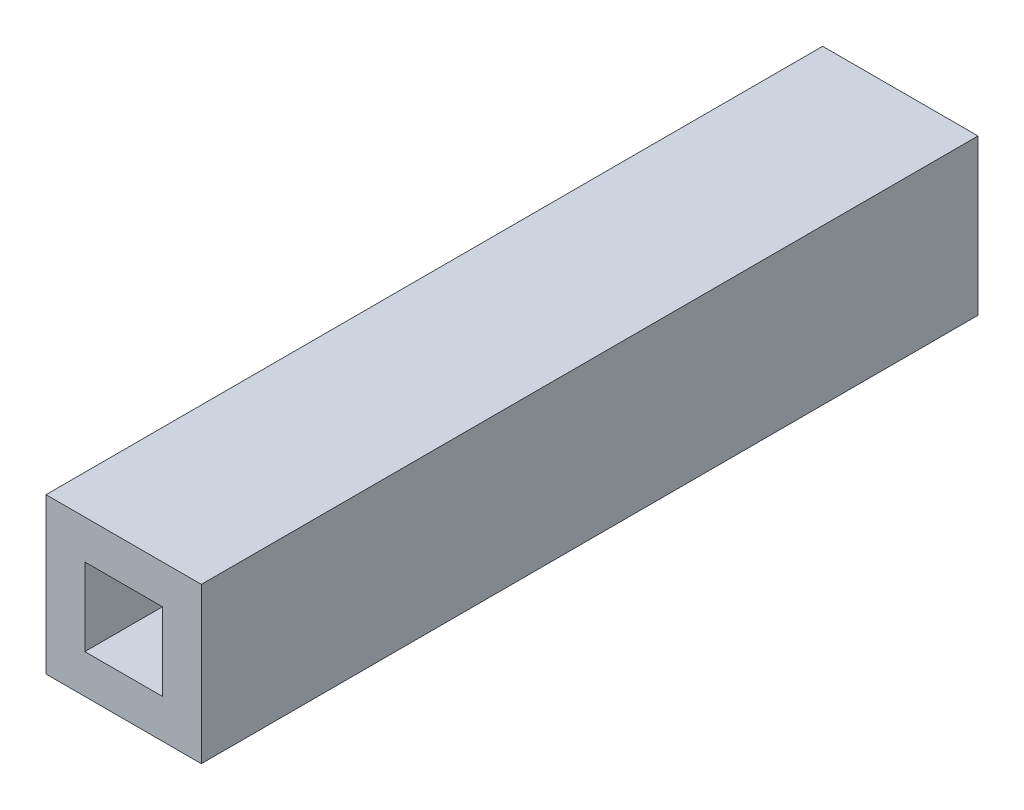
SolidWorks part; units mm, degrees
material "6063-O"
ref_plane "Front Plane" through (0, 0, 0) normal (0, 0, 1) x (1, 0, 0)
ref_plane "Top Plane" through (0, 0, 0) normal (0, 1, 0) x (1, 0, 0)
ref_plane "Right Plane" through (0, 0, 0) normal (1, 0, 0) x (0, 0, -1)
sketch "Sketch1" plane through (0, 0, 0) normal (0, 0, 1) x (1, 0, 0)
  line L1 (-10, -10) -> (10, -10)
  line L2 (-10, -10) -> (-10, 10)
  line L3 (-10, 10) -> (10, 10)
  line L4 (10, -10) -> (10, 10)
  line L5 (-10, -10) -> (10, 10) construction
  line L6 (-10, 10) -> (10, -10) construction
  point P0 (0, 0)
  dimension "D1" = 20
extrude "Extrude-Thin1" add sketch "Sketch1" along normal blind 100 thin thin type one direction reverse wall 5
